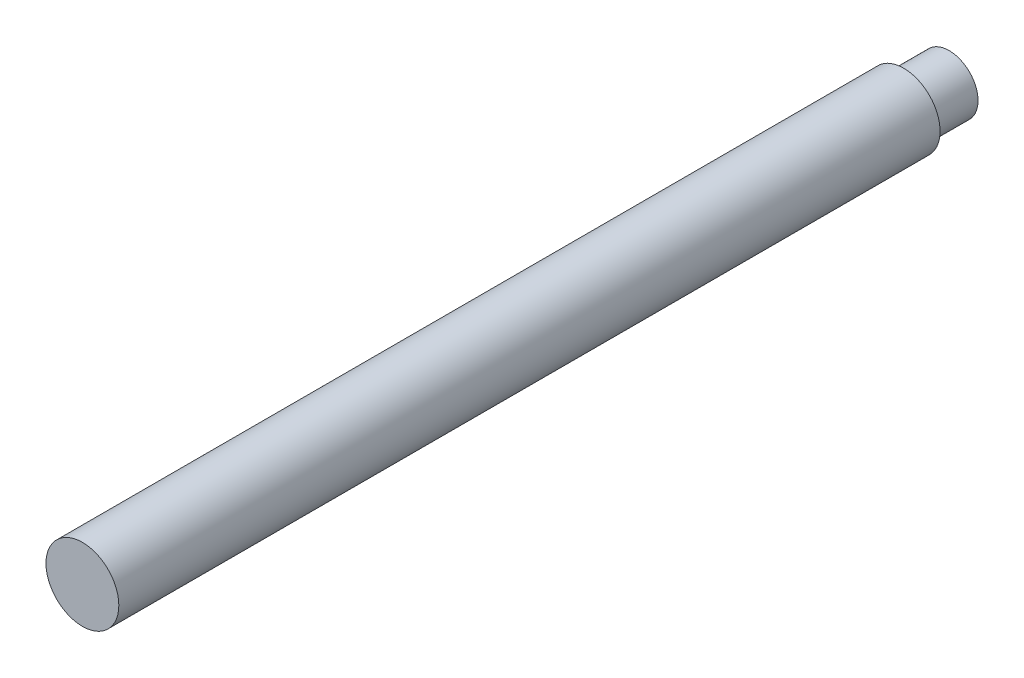
SolidWorks part; units mm, degrees
material "Plain Carbon Steel"
ref_plane "Front Plane" through (0, 0, 0) normal (0, 0, 1) x (1, 0, 0)
ref_plane "Top Plane" through (0, 0, 0) normal (0, 1, 0) x (1, 0, 0)
ref_plane "Right Plane" through (0, 0, 0) normal (1, 0, 0) x (0, 0, -1)
sketch "Sketch1" plane through (0, 0, 0) normal (0, 0, 1) x (1, 0, 0)
  circle A0 centre (0, 0) radius 4.0005
  dimension "D1" = 8.001
extrude "Boss-Extrude1" add sketch "Sketch1" along normal blind 95.25
sketch "Sketch2" plane through (0, 0, 0) normal (0, 0, -1) x (-1, 0, 0)
  circle A0 centre (0, 0) radius 3.175
  circle A1 centre (0, 0) radius 6.4669
  dimension "D1" = 6.35
extrude "Cut-Extrude1" cut sketch "Sketch2" against normal blind 5
